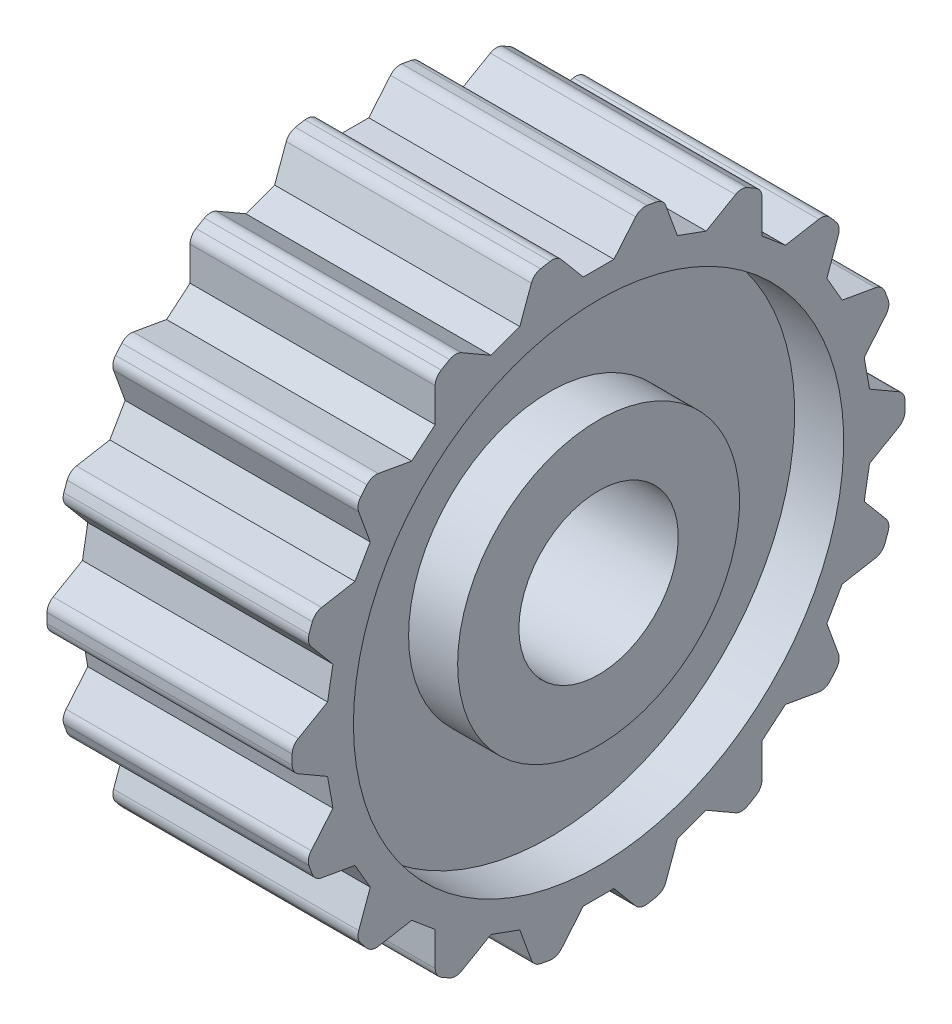
SolidWorks part; units mm, degrees
ref_plane "Front Plane" through (0, 0, 0) normal (0, 0, 1) x (1, 0, 0)
ref_plane "Top Plane" through (0, 0, 0) normal (0, 1, 0) x (1, 0, 0)
ref_plane "Right Plane" through (0, 0, 0) normal (1, 0, 0) x (0, 0, -1)
sketch "Sketch1" plane through (0, 0, 0) normal (0, 0, 1) x (1, 0, 0)
  line L0 (0, 0) -> (2.9972, 0) construction
  line L1 (0, 0) -> (0, 104.1413) construction
  line L2 (5.08, 5.842) -> (3.048, 5.842)
  line L3 (-5.08, 3.302) -> (5.08, 3.302)
  line L4 (5.08, 3.302) -> (5.08, 5.842)
  line L5 (3.048, 5.842) -> (3.048, 10.16)
  line L6 (3.048, 10.16) -> (5.08, 10.16)
  line L7 (5.08, 10.16) -> (5.08, 12.7)
  line L8 (5.08, 12.7) -> (-5.08, 12.7)
  line L9 (-5.08, 10.16) -> (-5.08, 12.7)
  line L10 (-3.048, 10.16) -> (-5.08, 10.16)
  line L11 (-3.048, 5.842) -> (-3.048, 10.16)
  line L12 (-5.08, 3.302) -> (-5.08, 5.842)
  line L13 (-5.08, 5.842) -> (-3.048, 5.842)
  point P11 (0, 12.7)
  point P18 (0, 3.302)
  dimension "D1" = 12.7
  dimension "D2" = 2.54
  dimension "D3" = 2.54
  dimension "D4" = 3.302
  dimension "D5" = 10.16
  dimension "D6" = 2.032
  dimension "D7" = 10.16
revolve "Revolve1" add sketch "Sketch1" angle 360 about L0
sketch "Sketch2" plane through (0, 0, 0) normal (1, 0, 0) x (0, 0, -1)
  line L0 (0, 0) -> (0, 22.6601) construction
  line L1 (0, 0) -> (3.2356, 18.3498) construction
  line L2 (0, 0) -> (-3.1345, 17.4557) construction
  line L4 (0.635, 11.2915) -> (1.9913, 12.9068)
  line L7 (-0.635, 11.2915) -> (0.635, 11.2915)
  line L8 (1.9913, 12.9068) -> (-1.9913, 12.9068)
  line L9 (-0.635, 11.2915) -> (-1.9913, 12.9068)
  point P3 (2.4164, 16.0154)
  point P8 (2.7171, 16.4297)
  point P11 (0, 13.3164)
  point P12 (0, 11.2915)
  point P13 (0, 12.9068)
  point P14 (0, 11.2915)
  point P15 (0, 0)
  point P16 (0, 0)
  point P17 (0.8324, 13.5711)
  point P18 (2.5344, 15.3681)
  point P19 (0, 0)
  point P20 (0, 0)
  point P21 (0.9463, 13.7154)
  point P22 (2.5602, 15.4403)
  point P23 (2.1016, 13.6866)
  point P24 (2.081, 13.0678)
  point P25 (1.8836, 13.0243)
  point P26 (0.6403, 11.2915)
  point P27 (1.9913, 12.9068)
  dimension "D1" = 20.18
  dimension "D2" = 1.27
extrude "Cut-Extrude1" cut sketch "Sketch2" against normal through all both and the other way through all
fillet "Fillet2" radius 0.508 2 edges at (0, 12.5831, -1.7194) (0, 12.5831, 1.7194)
pattern_circular "CirPattern1" count 18 over 360 about axis through (0, 0, 0) along (1, 0, 0) of "Fillet2", "Cut-Extrude1"
